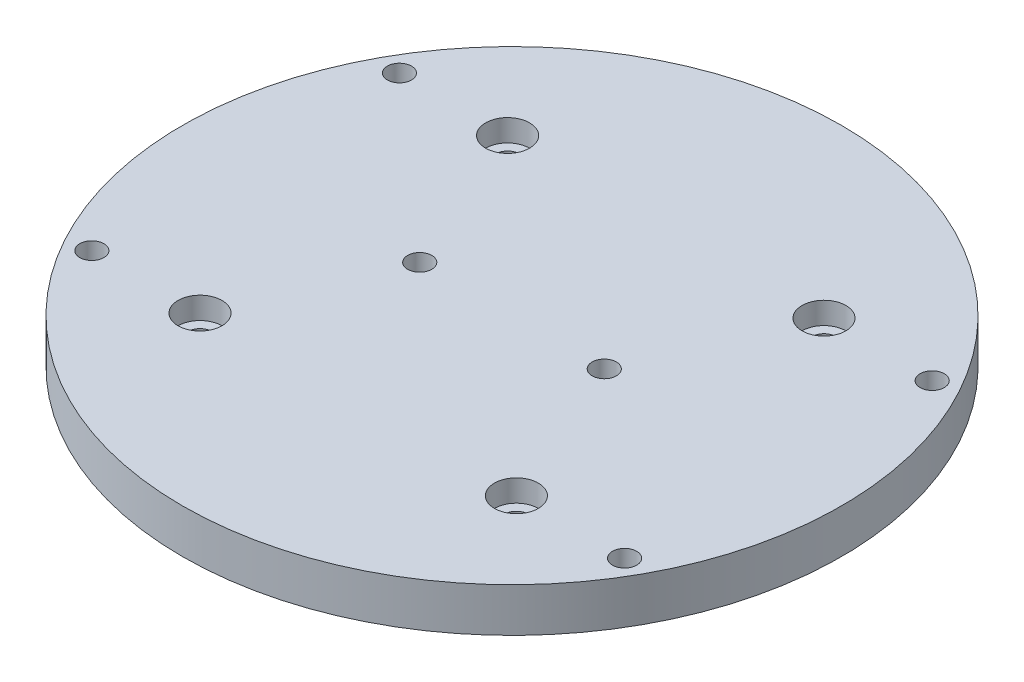
SolidWorks part; units mm, degrees
ref_plane "前视基准面" through (0, 0, 0) normal (0, 0, 1) x (1, 0, 0)
ref_plane "上视基准面" through (0, 0, 0) normal (0, 1, 0) x (1, 0, 0)
ref_plane "右视基准面" through (0, 0, 0) normal (1, 0, 0) x (0, 0, -1)
other "Configuration Table"
sketch "草图1" plane through (0, 0, 0) normal (0, 1, 0) x (1, 0, 0)
  circle A0 centre (0, 0) radius 75
  dimension "D1" = 150
extrude "凸台-拉伸1" add sketch "草图1" along normal blind 10
sketch "草图2" plane through (0, 10, 0) normal (0, 1, 0) x (1, 0, 0)
  line L0 (-104.1191, 0) -> (98.2134, 0) construction
  line L1 (0, 78.3782) -> (0, -83.3851) construction
  line L2 (36, 34.471) -> (36, -33.8291) construction
  line L3 (-36, 18.6798) -> (-36, -19.4501) construction
  line L4 (0, 0) -> (60.6218, 35) construction
  circle A0 centre (21, 0) radius 2.75
  circle A1 centre (-21, 0) radius 2.75
  circle A2 centre (36, 35) radius 2.75
  circle A3 centre (36, -35) radius 2.75
  circle A4 centre (-36, -35) radius 2.75
  circle A5 centre (-36, 35) radius 2.75
  circle A6 centre (60.6218, 35) radius 2.75
  circle A7 centre (60.6218, -35) radius 2.75
  circle A8 centre (-60.6218, -35) radius 2.75
  circle A9 centre (-60.6218, 35) radius 2.75
  dimension "D3" = 5.5
  dimension "D4" = 5.5
  dimension "D8" = 5.5
  dimension "D1" = 72
  dimension "D2" = 42
  dimension "D5" = 70
  dimension "D6" = 70
  dimension "D7" = 30
extrude "切除-拉伸1" cut sketch "草图2" against normal blind 27
sketch "草图3" plane through (0, 10, 0) normal (0, 1, 0) x (1, 0, 0)
  circle A0 centre (36, 35) radius 5
  circle A1 centre (36, -35) radius 5
  circle A2 centre (-36, -35) radius 5
  circle A3 centre (-36, 35) radius 5
  dimension "D1" = 10
extrude "切除-拉伸2" cut sketch "草图3" against normal blind 5
